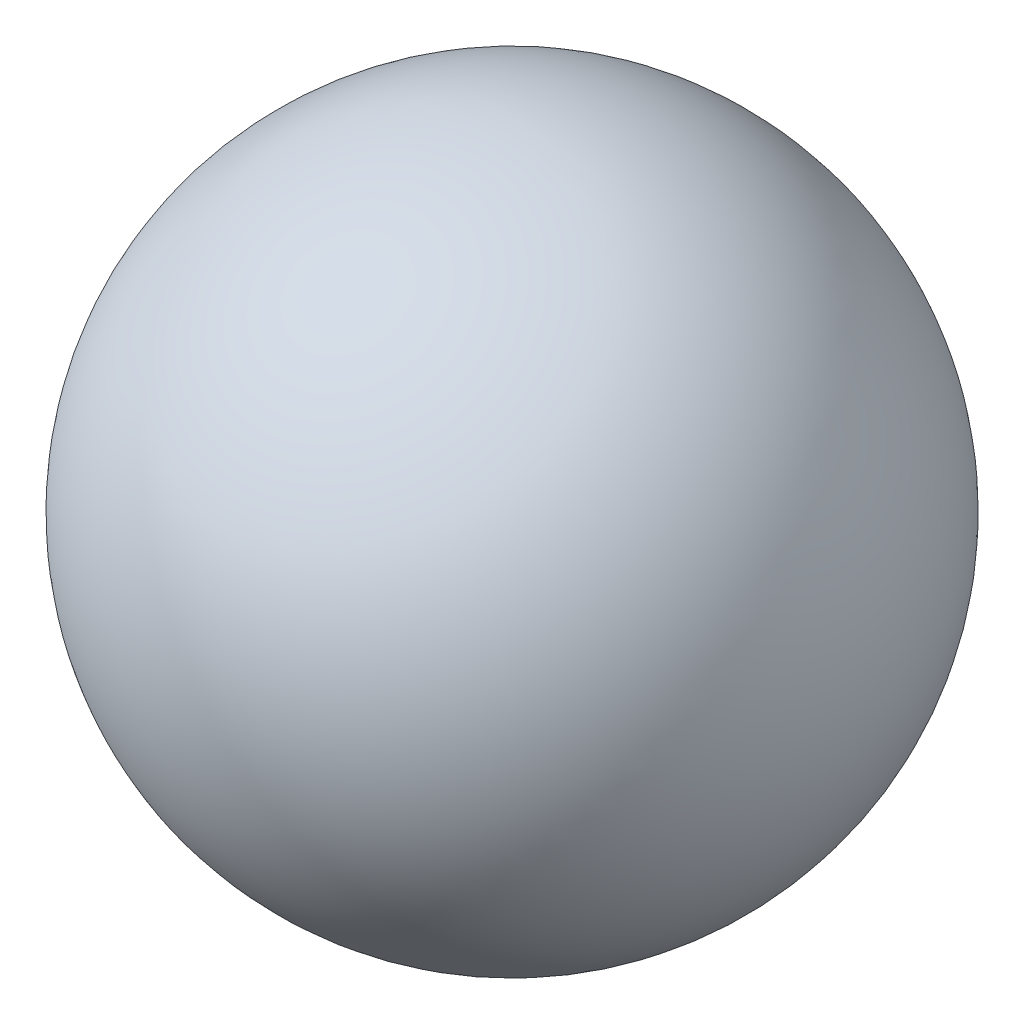
SolidWorks part; units mm, degrees
ref_plane "Front Plane" through (0, 0, 0) normal (0, 0, 1) x (1, 0, 0)
ref_plane "Top Plane" through (0, 0, 0) normal (0, 1, 0) x (1, 0, 0)
ref_plane "Right Plane" through (0, 0, 0) normal (1, 0, 0) x (0, 0, -1)
sketch "Sketch1" plane through (0, 0, 0) normal (0, 1, 0) x (1, 0, 0)
  line L0 (0, -15.1343) -> (0, 15.4997) construction
  line L1 (0, 6.35) -> (0, -6.35)
  arc A1 (0, -6.35) -> (0, 6.35) centre (0, 0) ccw
  dimension "D1" = 6.35
revolve "Revolve1" add sketch "Sketch1" angle 360 about L0
